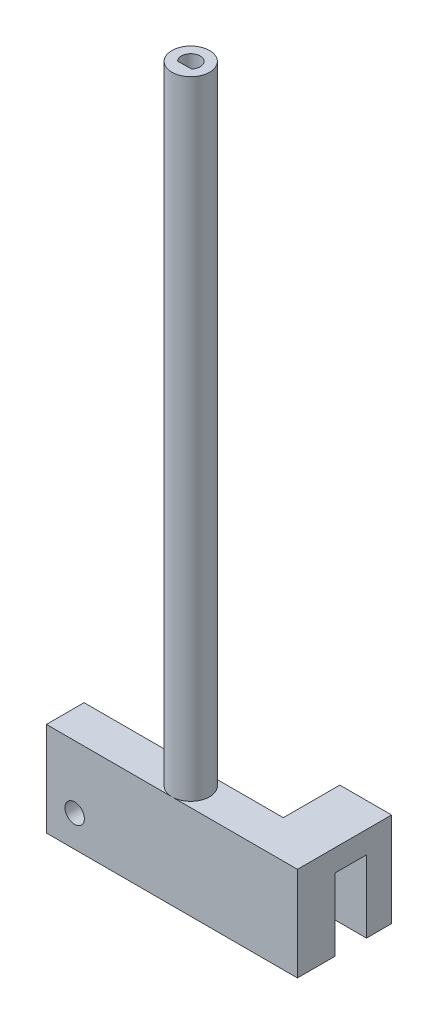
SolidWorks part; units mm, degrees
ref_plane "Front Plane" through (0, 0, 0) normal (0, 0, 1) x (1, 0, 0)
ref_plane "Top Plane" through (0, 0, 0) normal (0, 1, 0) x (1, 0, 0)
ref_plane "Right Plane" through (0, 0, 0) normal (1, 0, 0) x (0, 0, -1)
sketch "Sketch1" plane through (0, 0, 0) normal (0, 1, 0) x (1, 0, 0)
  circle A0 centre (0, 0) radius 3
  dimension "D1" = 6
extrude "Boss-Extrude1" add sketch "Sketch1" along normal blind 100
sketch "Sketch2" plane through (0, 100, 0) normal (0, 1, 0) x (1, 0, 0)
  line L0 (-1.1013, -1.0184) -> (1.1344, -0.9814)
  arc A0 (1.1344, -0.9814) -> (-1.1013, -1.0184) centre (0, 0) ccw
  dimension "D1" = 3
  dimension "D2" = 1
  dimension "D3" = 2.2358
extrude "Cut-Extrude1" cut sketch "Sketch2" against normal blind 6
sketch "Sketch3" plane through (0, 0, 0) normal (0, -1, 0) x (1, 0, 0)
  line L1 (-20, -3) -> (20, -3)
  line L2 (-20, -3) -> (-20, 3)
  line L3 (-20, 3) -> (20, 3)
  line L4 (20, -3) -> (20, 3)
  line L5 (-20, -3) -> (20, 3) construction
  line L6 (-20, 3) -> (20, -3) construction
  point P0 (0, 0)
  dimension "D1" = 6
  dimension "D2" = 40
extrude "Boss-Extrude2" add sketch "Sketch3" along normal blind 15
sketch "Sketch4" plane through (0, 0, -3) normal (0, 0, -1) x (-1, 0, 0)
  line L1 (20, -15) -> (-20, -15) construction
  circle A0 centre (15.5, -10) radius 1.55
  dimension "D2" = 3.1
  dimension "D1" = 15.5
  dimension "D3" = 5
extrude "Cut-Extrude2" cut sketch "Sketch4" against normal through all
sketch "Sketch6" plane through (0, 0, -3) normal (0, 0, -1) x (-1, 0, 0)
  line L0 (3.3, 0) -> (-3.3, 0) construction
  line L1 (-20, -15) -> (-11.75, -15)
  line L2 (-20, -15) -> (-20, 0)
  line L3 (-20, 0) -> (-11.75, 0)
  line L4 (-11.75, -15) -> (-11.75, 0)
  line L5 (20, -15) -> (20, 0) construction
  dimension "D1" = 31.75
extrude "Boss-Extrude3" add sketch "Sketch6" along normal blind 9
sketch "Sketch7" plane through (0, -15, 0) normal (0, -1, 0) x (1, 0, 0)
  line L0 (20, -12) -> (20, 3) construction
  line L1 (11.75, -3) -> (20, -3)
  line L2 (11.75, -3) -> (11.75, -8)
  line L3 (11.75, -8) -> (20, -8)
  line L4 (20, -3) -> (20, -8)
  dimension "D1" = 5
extrude "Cut-Extrude3" cut sketch "Sketch7" against normal blind 11.5
